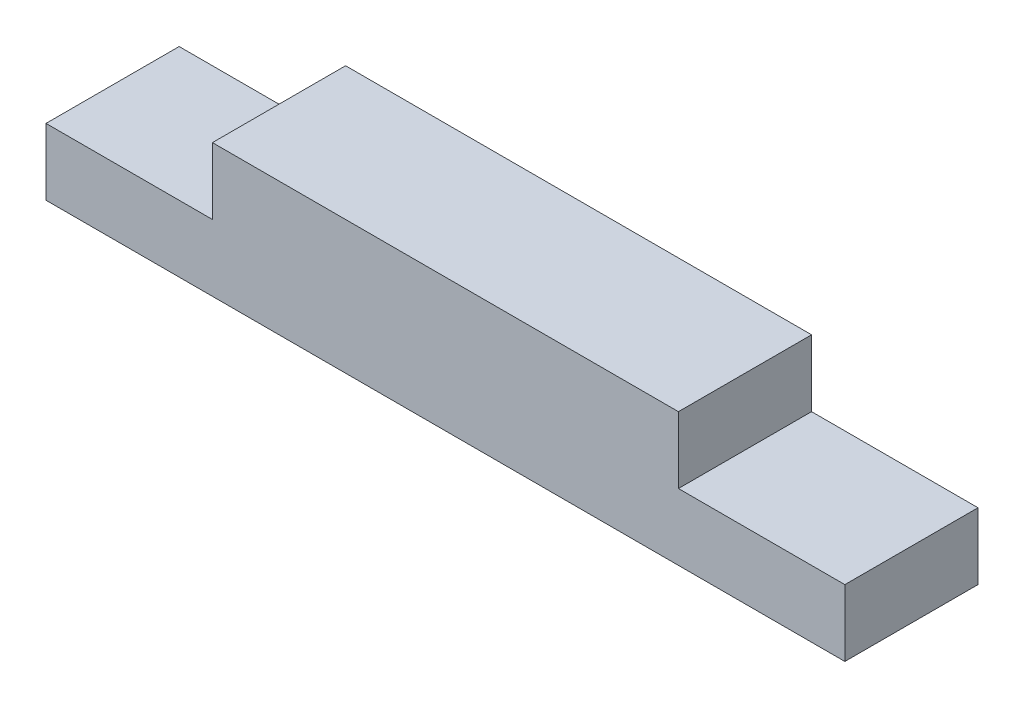
SolidWorks part; units mm, degrees
ref_plane "Front Plane" through (0, 0, 0) normal (0, 0, 1) x (1, 0, 0)
ref_plane "Top Plane" through (0, 0, 0) normal (0, 1, 0) x (1, 0, 0)
ref_plane "Right Plane" through (0, 0, 0) normal (1, 0, 0) x (0, 0, -1)
sketch "Sketch1" plane through (0, 0, 0) normal (0, 1, 0) x (1, 0, 0)
  line L1 (0, 0) -> (120, 0)
  line L2 (0, 0) -> (0, 20)
  line L3 (0, 20) -> (120, 20)
  line L4 (120, 0) -> (120, 20)
  dimension "D1" = 20
  dimension "D2" = 120
extrude "Boss-Extrude1" add sketch "Sketch1" along normal blind 20
sketch "Sketch2" plane through (0, 0, 0) normal (0, 0, 1) x (1, 0, 0)
  line L0 (0, 20) -> (45, 20)
  line L1 (0, 20) -> (120, 20) construction
  line L2 (120, 20) -> (75, 20)
  line L3 (0, 20) -> (0, 10)
  line L4 (0, 20) -> (0, 0) construction
  line L5 (120, 20) -> (120, 10)
  line L6 (0, 20) -> (25, 20)
  line L7 (0, 20) -> (0, 10)
  line L8 (0, 10) -> (25, 10)
  line L9 (25, 20) -> (25, 10)
  line L10 (120, 20) -> (120, 0) construction
  line L11 (120, 10) -> (95, 10)
  line L13 (120, 20) -> (95, 20)
  line L14 (120, 20) -> (120, 10)
  line L15 (120, 10) -> (95, 10)
  line L16 (95, 20) -> (95, 10)
  line M7 (120, 0) -> (120, 20)
  line M8 (120, 20) -> (0, 20)
  line M9 (0, 20) -> (0, 0)
  dimension "D1" = 45
  dimension "D2" = 45
  dimension "D3" = 10
  dimension "D4" = 25
  dimension "D5" = 25
extrude "Cut-Extrude1" cut sketch "Sketch2" against normal blind 20 contours L9 L0 L8 M9 | L16 L11 M8 M7
sketch "Sketch5" plane through (0, 0, -20) normal (0, 0, -1) x (-1, 0, 0)
  line L0 (-60, 0) -> (-60, 10)
  line L1 (-120, 0) -> (0, 0) construction
  circle A0 centre (-60, 10) radius 4.25
  dimension "D1" = 8.5
extrude "Cut-Extrude3" cut sketch "Sketch5" against normal blind 10
sketch "Sketch6" plane through (0, 0, 0) normal (0, -1, 0) x (-1, 0, 0)
  line L0 (-120, 10) -> (-80, 10)
  line L1 (-120, 0) -> (-120, 20) construction
  line L2 (0, 10) -> (-40, 10)
  line L3 (0, 20) -> (0, 0) construction
  circle A0 centre (-80, 10) radius 2.25
  circle A1 centre (-40, 10) radius 2.25
  dimension "D3" = 4.5
  dimension "D4" = 4.5
  dimension "D1" = 40
  dimension "D2" = 40
extrude "Cut-Extrude4" cut sketch "Sketch6" against normal blind 10
